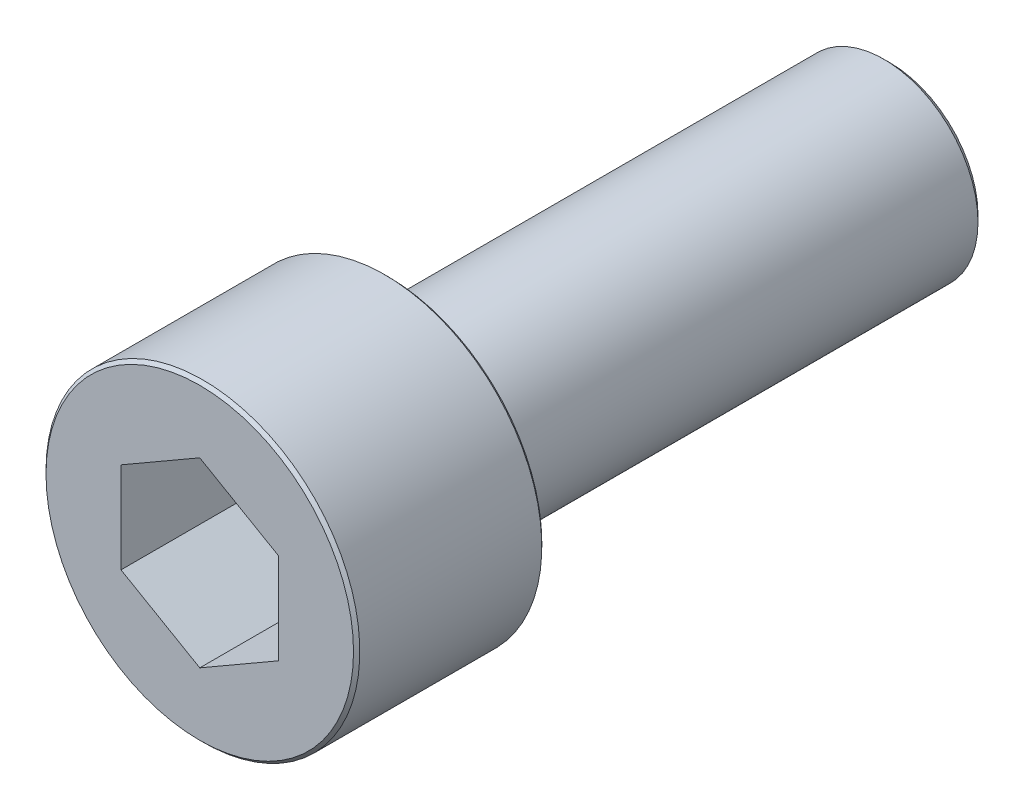
SolidWorks part; units mm, degrees
ref_plane "前视基准面" through (0, 0, 0) normal (0, 0, 1) x (1, 0, 0)
ref_plane "上视基准面" through (0, 0, 0) normal (0, 1, 0) x (1, 0, 0)
ref_plane "右视基准面" through (0, 0, 0) normal (1, 0, 0) x (0, 0, -1)
other "Configuration Table"
sketch "草图1" plane through (0, 0, 0) normal (0, 1, 0) x (1, 0, 0)
  line L0 (5, -16) -> (0, -16)
  line L1 (0, -16) -> (0, -22)
  line L2 (0, -22) -> (5, -22)
  line L3 (5, -22) -> (5, -16)
  line L4 (0, -16) -> (0, -22) construction
revolve "旋转1" add sketch "草图1" angle 360 about L4
sketch "草图2" plane through (0, 0, 16) normal (0, 0, -1) x (-1, 0, 0)
  circle A0 centre (0, 0) radius 3
extrude "凸台-拉伸1" add sketch "草图2" along normal blind 16
sketch "草图3" plane through (0, 0, 22) normal (0, 0, 1) x (1, 0, 0)
  line L0 (-2.51, -1.4491) -> (0, -2.8983)
  line L1 (0, -2.8983) -> (2.51, -1.4491)
  line L2 (2.51, -1.4491) -> (2.51, 1.4491)
  line L3 (2.51, 1.4491) -> (0, 2.8983)
  line L4 (0, 2.8983) -> (-2.51, 1.4491)
  line L5 (-2.51, 1.4491) -> (-2.51, -1.4491)
extrude "切除-拉伸1" cut sketch "草图3" against normal blind 4.5
chamfer "倒角1" distance 0.1 angle 45 2 edges at (5, 0, 16) (5, 0, 22)
chamfer "倒角2" distance 0.2 angle 45 1 edges at (-3, 0, 0)
